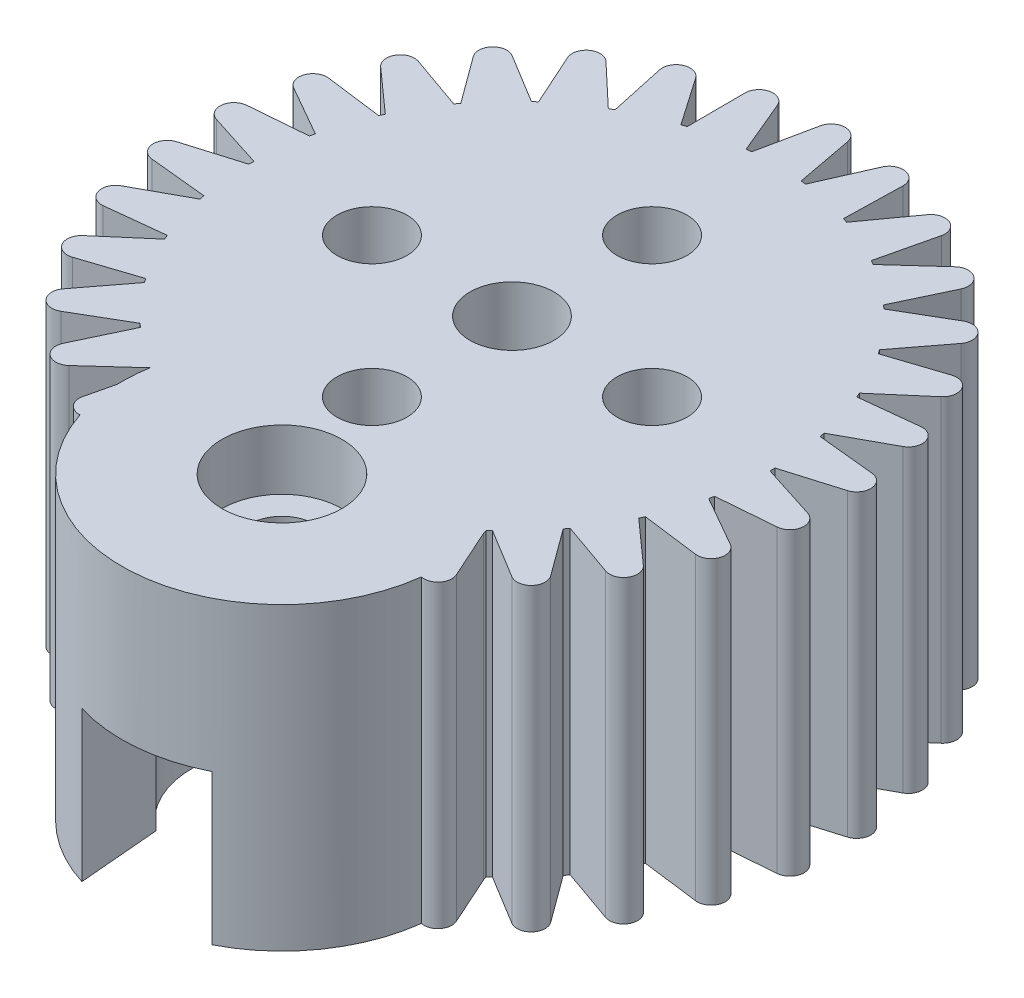
SolidWorks part; units mm, degrees
ref_plane "前视基准面" through (0, 0, 0) normal (0, 0, 1) x (1, 0, 0)
ref_plane "上视基准面" through (0, 0, 0) normal (0, 1, 0) x (1, 0, 0)
ref_plane "右视基准面" through (0, 0, 0) normal (1, 0, 0) x (0, 0, -1)
other "Configuration Table"
sketch "草图1" plane through (0, 0, 0) normal (0, 1, 0) x (1, 0, 0)
  line L0 (0, 0) -> (13.15, 0) construction
  line L1 (13.15, 0) -> (15.9283, 0.8312)
  line L2 (14.4192, 1.3769) -> (0, 0) construction
  line L3 (12.9124, 2.4887) -> (15.7978, 2.1983)
  line L5 (12.8626, -2.734) -> (15.7531, -2.4987)
  line L7 (13.1476, -0.2503) -> (15.9096, -1.1343)
  line L8 (12.0131, -5.3486) -> (14.8893, -5.7193)
  line L10 (12.8083, -2.9784) -> (15.3261, -4.4173)
  line L11 (10.6386, -7.7294) -> (13.3749, -8.69)
  line L13 (11.9091, -5.5763) -> (14.0728, -7.5072)
  line L14 (8.7991, -9.7724) -> (11.2758, -11.2809)
  line L16 (10.4895, -7.9305) -> (12.2044, -10.2691)
  line L17 (6.575, -11.3882) -> (8.684, -13.3787)
  line L19 (8.6114, -9.9381) -> (9.8027, -12.5821)
  line L20 (4.0636, -12.5064) -> (5.7126, -14.8919)
  line L22 (6.357, -11.5113) -> (6.9725, -14.3453)
  line L23 (1.3745, -13.078) -> (2.4916, -15.7542)
  line L25 (3.8248, -12.5815) -> (3.8376, -15.4815)
  line L26 (-1.3745, -13.078) -> (-0.8383, -15.928)
  line L28 (1.1253, -13.1018) -> (0.535, -15.941)
  line L29 (-4.0636, -12.5064) -> (-4.1316, -15.4056)
  line L31 (-1.6233, -13.0494) -> (-2.7911, -15.7039)
  line L32 (-6.575, -11.3882) -> (-7.2443, -14.2099)
  line L34 (-4.3009, -12.4268) -> (-5.9951, -14.7804)
  line L35 (-8.7991, -9.7724) -> (-10.0404, -12.3932)
  line L37 (-6.7906, -11.261) -> (-8.9371, -13.211)
  line L38 (-10.6386, -7.7294) -> (-12.3977, -10.0349)
  line L40 (-8.9835, -9.6031) -> (-11.4885, -11.0642)
  line L41 (-12.0131, -5.3486) -> (-14.2132, -7.238)
  line L43 (-10.7838, -7.5255) -> (-13.5379, -8.4338)
  line L44 (-12.8626, -2.734) -> (-15.4074, -4.1247)
  line L46 (-12.1128, -5.1189) -> (-14.9955, -5.4348)
  line L47 (-13.15, 0) -> (-15.9283, -0.8312)
  line L49 (-12.9124, -2.4887) -> (-15.7978, -2.1983)
  line L50 (-12.8626, 2.734) -> (-15.7531, 2.4987)
  line L52 (-13.1476, 0.2503) -> (-15.9096, 1.1343)
  line L53 (-12.0131, 5.3486) -> (-14.8893, 5.7193)
  line L55 (-12.8083, 2.9784) -> (-15.3261, 4.4173)
  line L56 (-10.6386, 7.7294) -> (-13.3749, 8.69)
  line L58 (-11.9091, 5.5763) -> (-14.0728, 7.5072)
  line L59 (-8.7991, 9.7724) -> (-11.2758, 11.2809)
  line L61 (-10.4895, 7.9305) -> (-12.2044, 10.2691)
  line L62 (-6.575, 11.3882) -> (-8.684, 13.3787)
  line L64 (-8.6114, 9.9381) -> (-9.8027, 12.5821)
  line L65 (-4.0636, 12.5064) -> (-5.7126, 14.8919)
  line L67 (-6.357, 11.5113) -> (-6.9725, 14.3453)
  line L68 (-1.3745, 13.078) -> (-2.4916, 15.7542)
  line L70 (-3.8248, 12.5815) -> (-3.8376, 15.4815)
  line L71 (1.3745, 13.078) -> (0.8383, 15.928)
  line L73 (-1.1253, 13.1018) -> (-0.535, 15.941)
  line L74 (4.0636, 12.5064) -> (4.1316, 15.4056)
  line L76 (1.6233, 13.0494) -> (2.7911, 15.7039)
  line L77 (6.575, 11.3882) -> (7.2443, 14.2099)
  line L79 (4.3009, 12.4268) -> (5.9951, 14.7804)
  line L80 (8.7991, 9.7724) -> (10.0404, 12.3932)
  line L82 (6.7906, 11.261) -> (8.9371, 13.211)
  line L83 (10.6386, 7.7294) -> (12.3977, 10.0349)
  line L85 (8.9835, 9.6031) -> (11.4885, 11.0642)
  line L86 (12.0131, 5.3486) -> (14.2132, 7.238)
  line L88 (10.7838, 7.5255) -> (13.5379, 8.4338)
  line L89 (12.8626, 2.734) -> (15.4074, 4.1247)
  line L91 (12.1128, 5.1189) -> (14.9955, 5.4348)
  arc A0 (6.7906, 11.261) -> (6.575, 11.3882) centre (0, 0) ccw
  arc A1 (15.7978, 2.1983) -> (15.9283, 0.8312) centre (15.7277, 1.5018) cw
  arc A2 (15.9096, -1.1343) -> (15.7531, -2.4987) centre (15.6963, -1.801) cw
  arc A3 (15.3261, -4.4173) -> (14.8893, -5.7193) centre (14.9788, -5.025) cw
  arc A4 (14.0728, -7.5072) -> (13.3749, -8.69) centre (13.6067, -8.0295) cw
  arc A5 (12.2044, -10.2691) -> (11.2758, -11.2809) centre (11.64, -10.683) cw
  arc A6 (9.8027, -12.5821) -> (8.684, -13.3787) centre (9.1645, -12.8697) cw
  arc A7 (6.9725, -14.3453) -> (5.7126, -14.8919) centre (6.2884, -14.4938) cw
  arc A8 (3.8376, -15.4815) -> (2.4916, -15.7542) centre (3.1376, -15.4846) cw
  arc A9 (0.535, -15.941) -> (-0.8383, -15.928) centre (-0.1504, -15.7985) cw
  arc A10 (-2.7911, -15.7039) -> (-4.1316, -15.4056) centre (-3.4318, -15.422) cw
  arc A11 (-5.9951, -14.7804) -> (-7.2443, -14.2099) centre (-6.5632, -14.3715) cw
  arc A12 (-8.9371, -13.211) -> (-10.0404, -12.3932) centre (-9.4078, -12.6929) cw
  arc A13 (-11.4885, -11.0642) -> (-12.3977, -10.0349) centre (-11.8412, -10.4595) cw
  arc A14 (-13.5379, -8.4338) -> (-14.2132, -7.238) centre (-13.7571, -7.769) cw
  arc A15 (-14.9955, -5.4348) -> (-15.4074, -4.1247) centre (-15.0718, -4.739) cw
  arc A16 (-15.7978, -2.1983) -> (-15.9283, -0.8312) centre (-15.7277, -1.5018) cw
  arc A17 (-15.9096, 1.1343) -> (-15.7531, 2.4987) centre (-15.6963, 1.801) cw
  arc A18 (-15.3261, 4.4173) -> (-14.8893, 5.7193) centre (-14.9788, 5.025) cw
  arc A19 (-14.0728, 7.5072) -> (-13.3749, 8.69) centre (-13.6067, 8.0295) cw
  arc A20 (-12.2044, 10.2691) -> (-11.2758, 11.2809) centre (-11.64, 10.683) cw
  arc A21 (-9.8027, 12.5821) -> (-8.684, 13.3787) centre (-9.1645, 12.8697) cw
  arc A22 (-6.9725, 14.3453) -> (-5.7126, 14.8919) centre (-6.2884, 14.4938) cw
  arc A23 (-3.8376, 15.4815) -> (-2.4916, 15.7542) centre (-3.1376, 15.4846) cw
  arc A24 (-0.535, 15.941) -> (0.8383, 15.928) centre (0.1504, 15.7985) cw
  arc A25 (2.7911, 15.7039) -> (4.1316, 15.4056) centre (3.4318, 15.422) cw
  arc A26 (5.9951, 14.7804) -> (7.2443, 14.2099) centre (6.5632, 14.3715) cw
  arc A27 (8.9371, 13.211) -> (10.0404, 12.3932) centre (9.4078, 12.6929) cw
  arc A28 (11.4885, 11.0642) -> (12.3977, 10.0349) centre (11.8412, 10.4595) cw
  arc A29 (13.5379, 8.4338) -> (14.2132, 7.238) centre (13.7571, 7.769) cw
  arc A30 (14.9955, 5.4348) -> (15.4074, 4.1247) centre (15.0718, 4.739) cw
  arc A31 (4.3009, 12.4268) -> (4.0636, 12.5064) centre (0, 0) ccw
  arc A32 (8.9835, 9.6031) -> (8.7991, 9.7724) centre (0, 0) ccw
  arc A33 (10.7838, 7.5255) -> (10.6386, 7.7294) centre (0, 0) ccw
  arc A34 (12.1128, 5.1189) -> (12.0131, 5.3486) centre (0, 0) ccw
  arc A35 (1.6233, 13.0494) -> (1.3745, 13.078) centre (0, 0) ccw
  arc A36 (-1.1253, 13.1018) -> (-1.3745, 13.078) centre (0, 0) ccw
  arc A37 (-3.8248, 12.5815) -> (-4.0636, 12.5064) centre (0, 0) ccw
  arc A38 (-6.357, 11.5113) -> (-6.575, 11.3882) centre (0, 0) ccw
  arc A39 (-8.6114, 9.9381) -> (-8.7991, 9.7724) centre (0, 0) ccw
  arc A40 (-10.4895, 7.9305) -> (-10.6386, 7.7294) centre (0, 0) ccw
  arc A41 (-11.9091, 5.5763) -> (-12.0131, 5.3486) centre (0, 0) ccw
  arc A42 (-12.8083, 2.9784) -> (-12.8626, 2.734) centre (0, 0) ccw
  arc A43 (-13.1476, 0.2503) -> (-13.15, 0) centre (0, 0) ccw
  arc A44 (-12.9124, -2.4887) -> (-12.8626, -2.734) centre (0, 0) ccw
  arc A45 (-12.1128, -5.1189) -> (-12.0131, -5.3486) centre (0, 0) ccw
  arc A46 (-10.7838, -7.5255) -> (-10.6386, -7.7294) centre (0, 0) ccw
  arc A47 (-8.9835, -9.6031) -> (-8.7991, -9.7724) centre (0, 0) ccw
  arc A48 (-6.7906, -11.261) -> (-6.575, -11.3882) centre (0, 0) ccw
  arc A49 (-4.3009, -12.4268) -> (-4.0636, -12.5064) centre (0, 0) ccw
  arc A50 (-1.6233, -13.0494) -> (-1.3745, -13.078) centre (0, 0) ccw
  arc A51 (1.1253, -13.1018) -> (1.3745, -13.078) centre (0, 0) ccw
  arc A52 (3.8248, -12.5815) -> (4.0636, -12.5064) centre (0, 0) ccw
  arc A53 (6.357, -11.5113) -> (6.575, -11.3882) centre (0, 0) ccw
  arc A54 (8.6114, -9.9381) -> (8.7991, -9.7724) centre (0, 0) ccw
  arc A55 (10.4895, -7.9305) -> (10.6386, -7.7294) centre (0, 0) ccw
  arc A56 (11.9091, -5.5763) -> (12.0131, -5.3486) centre (0, 0) ccw
  arc A57 (12.8083, -2.9784) -> (12.8626, -2.734) centre (0, 0) ccw
  arc A58 (13.1476, -0.2503) -> (13.15, 0) centre (0, 0) ccw
  arc A59 (12.9124, 2.4887) -> (12.8626, 2.734) centre (0, 0) ccw
  circle A60 centre (0, 0) radius 2.1
  circle A61 centre (0, 0) radius 7 construction
  circle A62 centre (0, 7) radius 1.75
  circle A63 centre (7, 0) radius 1.75
  circle A64 centre (0, -7) radius 1.75
  circle A65 centre (-7, 0) radius 1.75
  point P157 (0, 0)
  point P225 (0, 0)
  dimension "D1" = 26.3
  dimension "D2" = 2.9
  dimension "0.7" = 0.7
  dimension "D6" = 4.2
  dimension "D7" = 14
  dimension "D8" = 3.5
  dimension "D3" = 2.5
  dimension "D5" = 30
  dimension "D9" = 4
extrude "凸台-拉伸1" add sketch "草图1" along normal blind 15
sketch "草图2" plane through (0, 0, 0) normal (0, -1, 0) x (1, 0, 0)
  line L0 (0, 0) -> (1.768, 20.5506) construction
  line L1 (0, 7) -> (0.5978, 6.9486)
  line L2 (1.768, 20.5506) -> (9.7385, 19.8649) construction
  line L3 (-6.8066, 11.2513) -> (8.6283, 9.9235) construction
  line L8 (9.7385, 19.8649) -> (8.3671, 3.9238) construction
  line L10 (8.3671, 3.9238) -> (-7.574, 5.2952) construction
  line L11 (-7.0954, 10.8581) -> (-6.2026, 21.2363) construction
  line L12 (-6.2026, 21.2363) -> (1.768, 20.5506) construction
  circle A0 centre (0, 7) radius 1.75 construction
  arc A2 (8.6283, 9.9235) -> (-6.8066, 11.2513) centre (1.0823, 12.58) ccw
  arc A3 (8.6283, 9.9235) -> (-6.8066, 11.2513) centre (0, 0) ccw
  dimension "D1" = 0.6
  dimension "D2" = 16
  dimension "D3" = 16
  dimension "D4" = 10
extrude "凸台-拉伸4" add sketch "草图2" against normal blind 15 contours A3 A2
sketch "草图5" plane through (0, 0, 0) normal (0, -1, 0) x (1, 0, 0)
  line L1 (-1.6192, 16.1789) -> (4.3587, 15.6646) construction
  line L2 (-1.6192, 16.1789) -> (-1.271, 20.2261)
  line L3 (4.3587, 15.6646) -> (4.7069, 19.7118)
  line L4 (0, 0) -> (1.0823, 12.58) construction
  arc A0 (-1.6192, 16.1789) -> (-0.8649, 8.5231) centre (1.0823, 12.58) ccw
  arc A1 (-6.9142, 12.8181) -> (-6.8114, 11.2799) centre (1.0823, 12.58) ccw construction
  arc A5 (4.7069, 19.7118) -> (-1.271, 20.2261) centre (1.0823, 12.58) ccw
  arc A6 (1.3716, 8.0893) -> (-0.8649, 8.5231) centre (0, 7) ccw
  arc A7 (1.3716, 8.0893) -> (4.3587, 15.6646) centre (1.0823, 12.58) ccw
  dimension "D1" = 4.5
  dimension "D2" = 6
extrude "切除-拉伸2" cut sketch "草图5" against normal blind 7.5
sketch "草图6" plane through (0, 15, 0) normal (0, 1, 0) x (1, 0, 0)
  circle A0 centre (1.0823, -12.58) radius 3
  dimension "D1" = 6
extrude "切除-拉伸3" cut sketch "草图6" against normal blind 3
sketch "草图7" plane through (0, 7.5, 0) normal (0, -1, 0) x (1, 0, 0)
  circle A0 centre (1.0823, 12.58) radius 1.65
  dimension "D1" = 3.3
extrude "切除-拉伸4" cut sketch "草图7" against normal blind 7.5
